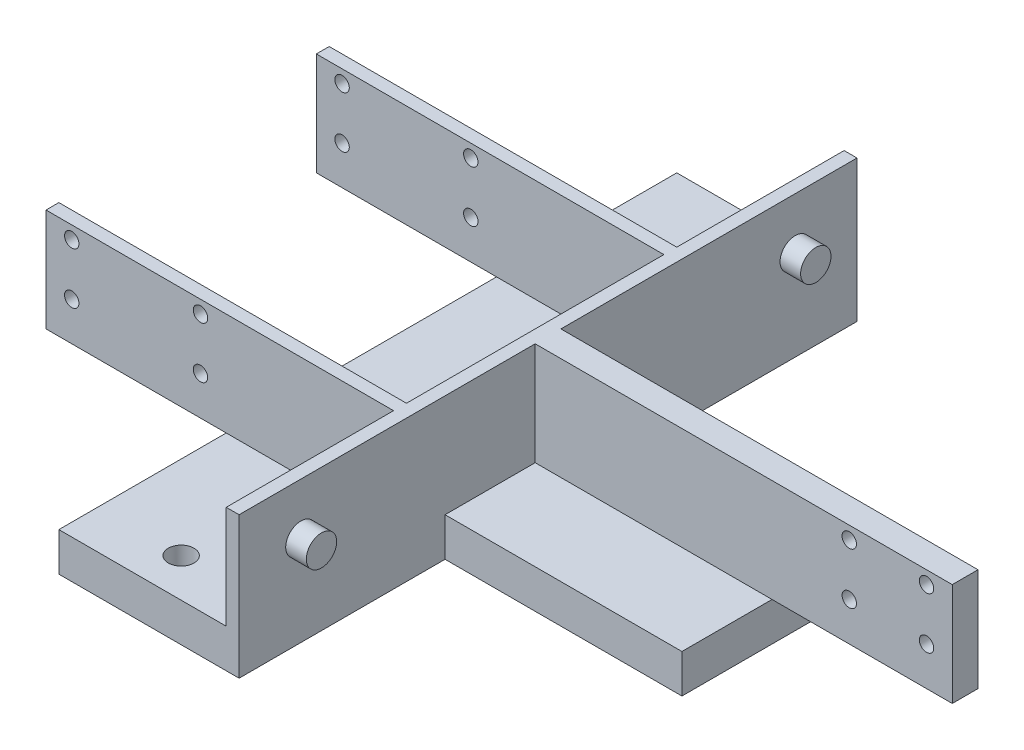
SolidWorks part; units mm, degrees
ref_plane "Front Plane" through (0, 0, 0) normal (0, 0, 1) x (1, 0, 0)
ref_plane "Top Plane" through (0, 0, 0) normal (0, 1, 0) x (1, 0, 0)
ref_plane "Right Plane" through (0, 0, 0) normal (1, 0, 0) x (0, 0, -1)
sketch "Sketch1" plane through (0, 0, 0) normal (0, 1, 0) x (1, 0, 0)
  line L1 (0, 60) -> (35, 60)
  line L2 (0, 60) -> (0, -60)
  line L3 (0, -60) -> (35, -60)
  line L4 (35, 60) -> (35, -60)
  line L5 (35, 20) -> (81, 20)
  line L6 (35, 20) -> (35, -20)
  line L7 (35, -20) -> (81, -20)
  line L8 (81, 20) -> (81, -20)
  point P4 (0, 0)
  point P10 (81, 0)
  dimension "D1" = 35
  dimension "D2" = 120
  dimension "D3" = 46
  dimension "D4" = 40
extrude "Boss-Extrude1" add sketch "Sketch1" along normal blind 7.5 contours L4 L1 L2 L3 | L8 L5 L4 L7
sketch "Sketch2" plane through (0, 7.5, 0) normal (0, 1, 0) x (1, 0, 0)
  line L0 (0, -60) -> (35, -60) construction
  line L1 (35, 60) -> (32.5, 60)
  line L2 (35, 60) -> (35, -60)
  line L3 (35, -60) -> (32.5, -60)
  line L4 (32.5, 60) -> (32.5, -60)
  line L6 (35, -2.5) -> (116, -2.5)
  line L7 (35, -2.5) -> (35, 2.5)
  line L8 (35, 2.5) -> (116, 2.5)
  line L9 (116, -2.5) -> (116, 2.5)
  line L11 (81, 20) -> (81, -20) construction
  line L12 (32.5, 27.5) -> (-35, 27.5)
  line L13 (32.5, 27.5) -> (32.5, 25)
  line L14 (32.5, 25) -> (-35, 25)
  line L15 (-35, 27.5) -> (-35, 25)
  line L16 (-1.25, 25) -> (-1.25, -25) construction
  line L17 (32.5, -25) -> (-35, -25)
  line L18 (32.5, -25) -> (32.5, -27.5)
  line L19 (32.5, -27.5) -> (-35, -27.5)
  line L20 (-35, -25) -> (-35, -27.5)
  line L21 (0, 60) -> (0, -60) construction
  point P11 (35, 0)
  point P27 (-1.25, 0)
  line M12 (81, -20) -> (81, 20)
  dimension "D1" = 2.5
  dimension "D2" = 5
  dimension "D3" = 35
  dimension "D4" = 2.5
  dimension "D5" = 50
  dimension "D6" = 35
extrude "Boss-Extrude2" add sketch "Sketch2" along normal blind 20 contours L8 L2 L6 M12 | L6 L9 L8 M12 | L13 L12 L15 L14 | L18 L17 L20 L19
sketch "Sketch3" plane through (0, 0, 2.5) normal (0, 0, 1) x (1, 0, 0)
  line L0 (111, 25) -> (96, 25) construction
  line L1 (96, 25) -> (96, 15) construction
  line L2 (96, 15) -> (111, 15) construction
  line L3 (111, 15) -> (111, 25) construction
  line L5 (116, 27.5) -> (116, 7.5) construction
  circle A0 centre (111, 25) radius 1.4
  circle A1 centre (111, 15) radius 1.4
  circle A2 centre (96, 15) radius 1.4
  circle A3 centre (96, 25) radius 1.4
  dimension "D1" = 2.8
  dimension "D2" = 10
  dimension "D3" = 15
  dimension "D5" = 5
extrude "Cut-Extrude1" cut sketch "Sketch3" against normal blind 5
sketch "Sketch5" plane through (35, 0, 0) normal (1, 0, 0) x (0, 0, -1)
  line L0 (0, 37.4256) -> (0, -6.8655) construction
  line L1 (-60, 27.5) -> (-60, 0) construction
  line L3 (-2.5, 27.5) -> (-60, 27.5) construction
  circle A0 centre (-48, 17.5) radius 2.95
  circle A1 centre (48, 17.5) radius 2.95
  dimension "D1" = 5.9
  dimension "D2" = 12
  dimension "D3" = 10
extrude "Boss-Extrude4" add sketch "Sketch5" along normal blind 4
sketch "Sketch6" plane through (0, 0, 27.5) normal (0, 0, 1) x (1, 0, 0)
  line L0 (-30, 25) -> (-30, 15) construction
  line L1 (-30, 15) -> (-5, 15) construction
  line L2 (-5, 15) -> (-5, 25) construction
  line L3 (-5, 25) -> (-30, 25) construction
  line L4 (-35, 27.5) -> (-35, 7.5) construction
  line L5 (32.5, 27.5) -> (-35, 27.5) construction
  circle A0 centre (-30, 25) radius 1.4
  circle A1 centre (-5, 25) radius 1.4
  circle A2 centre (-30, 15) radius 1.4
  circle A3 centre (-5, 15) radius 1.4
  dimension "D5" = 2.8
  dimension "D1" = 10
  dimension "D2" = 25
  dimension "D3" = 5
  dimension "D4" = 2.5
extrude "Cut-Extrude2" cut sketch "Sketch6" against normal blind 60
sketch "Sketch7" plane through (0, 7.5, 0) normal (0, 1, 0) x (1, 0, 0)
  line L0 (0, 60) -> (32.5, 60) construction
  line L1 (0, 43.75) -> (32.5, 43.75) construction
  line L2 (0, 60) -> (0, 27.5) construction
  line L3 (32.5, 60) -> (32.5, 27.5) construction
  line L4 (0, 0) -> (126.4537, 0) construction
  line L5 (0, 25) -> (0, -25) construction
  line L6 (0, -43.75) -> (32.5, -43.75) construction
  circle A0 centre (16.25, 52.5) radius 2.5
  circle A1 centre (16.25, 35) radius 2.5
  circle A2 centre (16.25, -35) radius 2.5
  circle A3 centre (16.25, -52.5) radius 2.5
  point P4 (16.25, 60)
  dimension "D1" = 5
  dimension "D2" = 7.5
extrude "Cut-Extrude3" cut sketch "Sketch7" against normal blind 10
